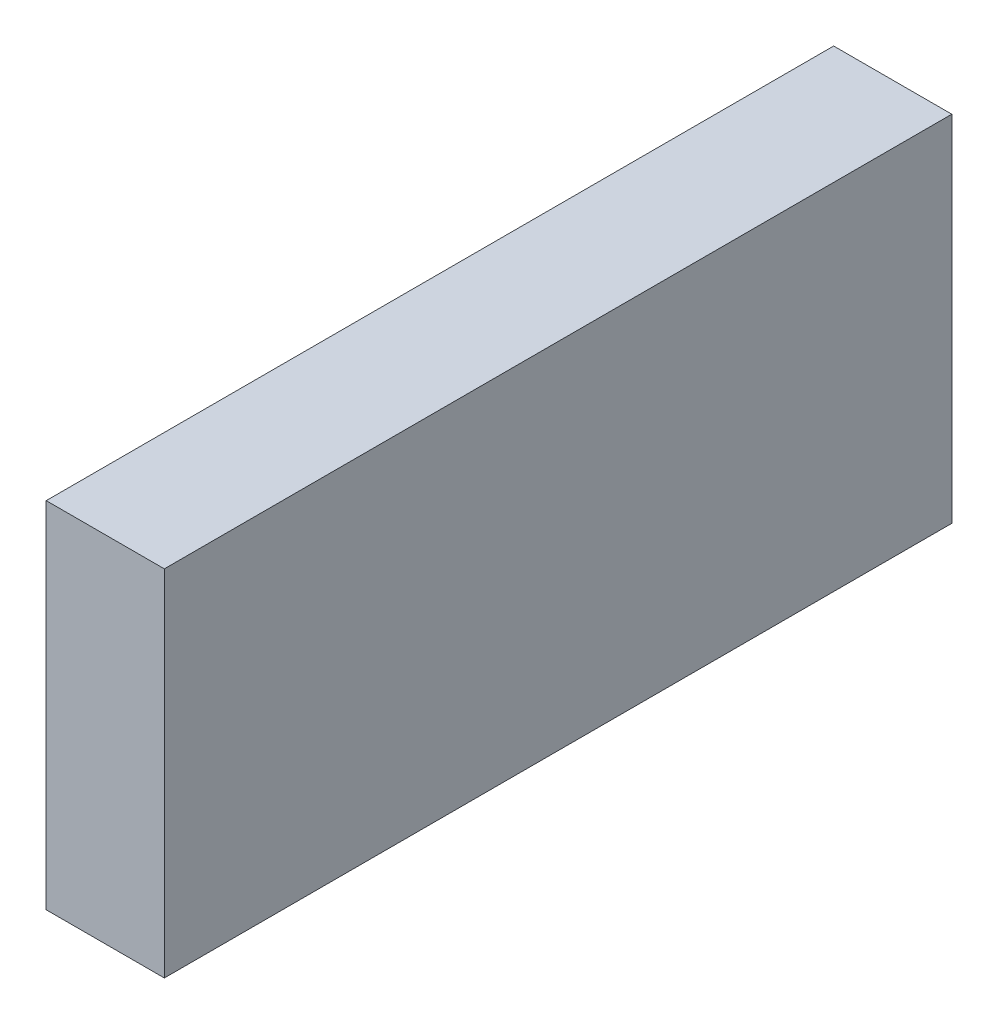
SolidWorks part; units mm, degrees
ref_plane "Front Plane" through (0, 0, 0) normal (0, 0, 1) x (1, 0, 0)
ref_plane "Top Plane" through (0, 0, 0) normal (0, 1, 0) x (1, 0, 0)
ref_plane "Right Plane" through (0, 0, 0) normal (1, 0, 0) x (0, 0, -1)
sketch "Sketch1" plane through (0, 0, 0) normal (0, 0, 1) x (1, 0, 0)
  line L1 (-15, -45) -> (15, -45)
  line L2 (-15, -45) -> (-15, 45)
  line L3 (-15, 45) -> (15, 45)
  line L4 (15, -45) -> (15, 45)
  line L5 (-15, -45) -> (15, 45) construction
  line L6 (-15, 45) -> (15, -45) construction
  point P0 (0, 0)
  dimension "D1" = 90
  dimension "D2" = 30
extrude "Boss-Extrude1" add sketch "Sketch1" along normal mid plane 200
